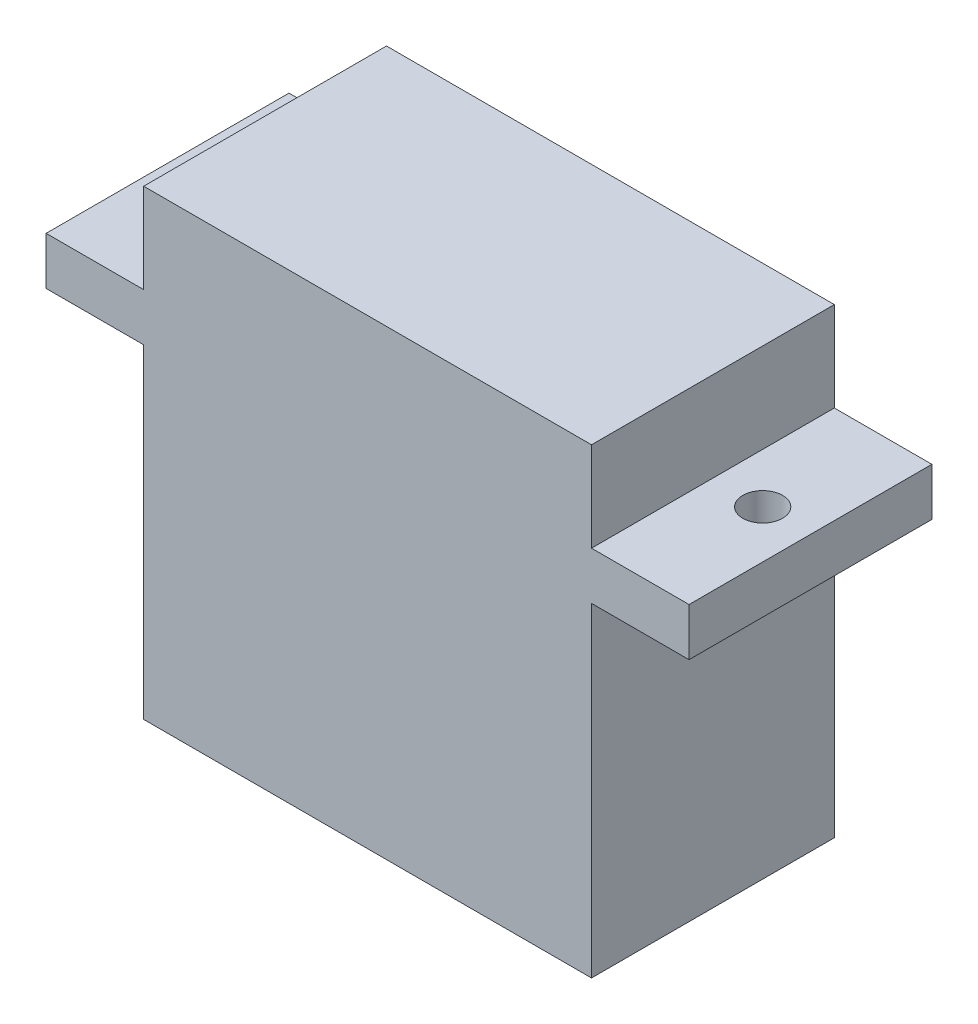
SolidWorks part; units mm, degrees
ref_plane "前基準面" through (0, 0, 0) normal (0, 0, 1) x (1, 0, 0)
ref_plane "上基準面" through (0, 0, 0) normal (0, 1, 0) x (1, 0, 0)
ref_plane "右基準面" through (0, 0, 0) normal (1, 0, 0) x (0, 0, -1)
sketch "草圖2" plane through (0, 0, 0) normal (0, 1, 0) x (1, 0, 0)
  line L0 (-13.75, 0) -> (13.75, 0) construction
  line L1 (-16.15, 6.1) -> (16.15, 6.1)
  line L2 (-16.15, 6.1) -> (-16.15, -6.1)
  line L3 (-16.15, -6.1) -> (16.15, -6.1)
  line L4 (16.15, 6.1) -> (16.15, -6.1)
  line L5 (-16.15, 6.1) -> (16.15, -6.1) construction
  line L6 (-16.15, -6.1) -> (16.15, 6.1) construction
  circle A0 centre (-13.75, 0) radius 1
  circle A1 centre (13.75, 0) radius 1
  point P1 (0, 0)
  dimension "D3" = 2
  dimension "D1" = 32.3
  dimension "D2" = 12.2
  dimension "D4" = 27.5
extrude "填料-伸長1" add sketch "草圖2" along normal blind 2.4
sketch "草圖3" plane through (0, 0, 0) normal (0, -1, 0) x (1, 0, 0)
  line L0 (16.15, -6.1) -> (-16.15, -6.1) construction
  line L1 (-11.25, 6.1) -> (11.25, 6.1)
  line L2 (-11.25, 6.1) -> (-11.25, -6.1)
  line L3 (-11.25, -6.1) -> (11.25, -6.1)
  line L4 (11.25, 6.1) -> (11.25, -6.1)
  line L5 (-11.25, 6.1) -> (11.25, -6.1) construction
  line L6 (-11.25, -6.1) -> (11.25, 6.1) construction
  point P0 (0, 0)
  dimension "D1" = 22.5
extrude "填料-伸長2" add sketch "草圖3" along normal blind 16.3 and the other way blind 6.9
